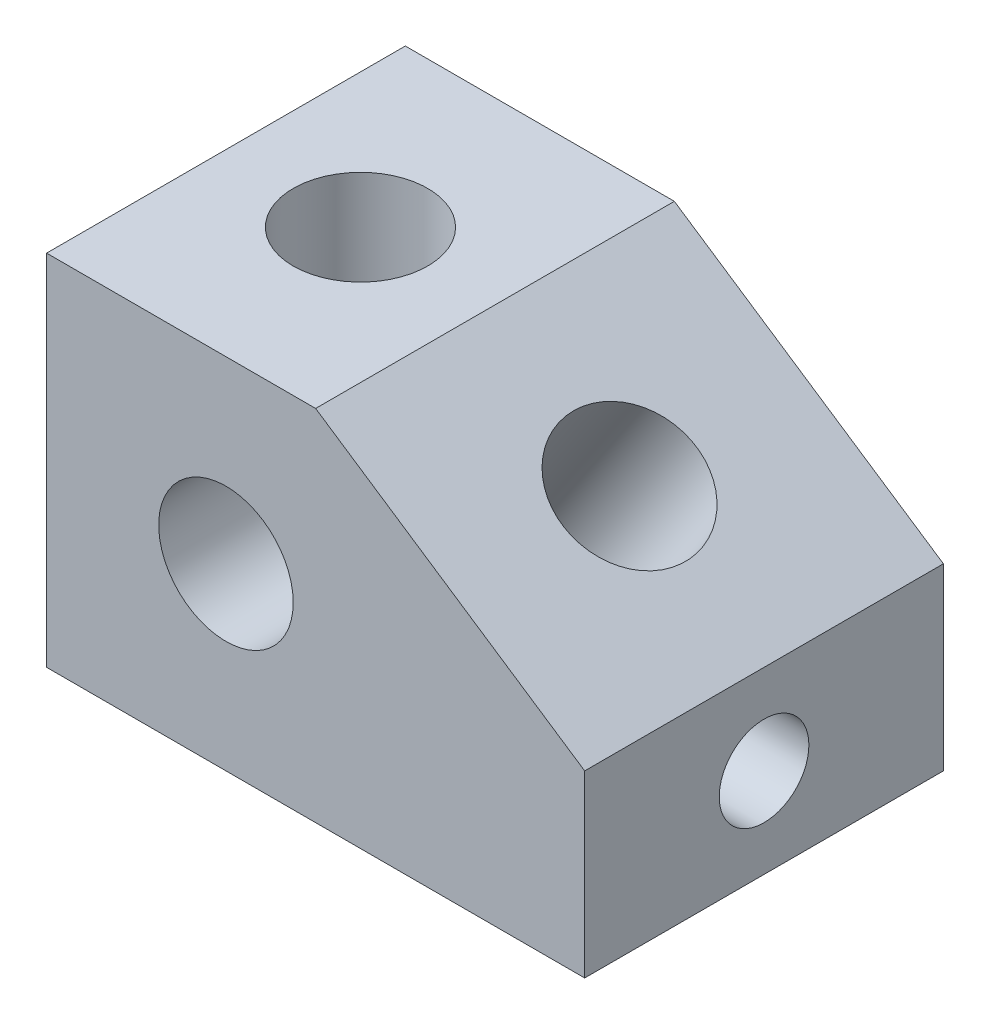
SolidWorks part; units mm, degrees
ref_plane "정면" through (0, 0, 0) normal (0, 0, 1) x (1, 0, 0)
ref_plane "윗면" through (0, 0, 0) normal (0, 1, 0) x (1, 0, 0)
ref_plane "우측면" through (0, 0, 0) normal (1, 0, 0) x (0, 0, -1)
sketch "스케치1" plane through (0, 0, 0) normal (0, 0, 1) x (1, 0, 0)
  line L0 (-34.3086, 0) -> (25.6914, 0)
  line L1 (25.6914, 0) -> (25.6914, 20)
  line L2 (-34.3086, 0) -> (-34.3086, 40)
  line L3 (-34.3086, 40) -> (-4.3086, 40)
  line L4 (-4.3086, 40) -> (25.6914, 20)
  dimension "D1" = 30
  dimension "D2" = 30
  dimension "D3" = 20
  dimension "D4" = 20
extrude "보스-돌출1" add sketch "스케치1" along normal blind 40
sketch "스케치2" plane through (0, 0, 40) normal (0, 0, 1) x (1, 0, 0)
  circle A0 centre (-14.3086, 20) radius 7.5
  point P2 (0, 0)
  dimension "D1" = 20
  dimension "D2" = 15
  dimension "D3" = 20
extrude "컷-돌출1" cut sketch "스케치2" against normal blind 40
sketch "스케치4" plane through (0, 40, 0) normal (0, 1, 0) x (1, 0, 0)
  line L0 (-34.3086, -40) -> (-34.3086, 0) construction
  circle A0 centre (-19.3086, -20) radius 7.5
  point P4 (0, 0)
  point P5 (-19.3086, -20)
  dimension "D1" = 15
  dimension "D2" = 15
  dimension "D3" = 20
extrude "컷-돌출2" cut sketch "스케치4" against normal through all
sketch "스케치5" plane through (25.6914, 0, 0) normal (1, 0, 0) x (0, 0, -1)
  circle A0 centre (-20, 10) radius 5
extrude "컷-돌출3" cut sketch "스케치5" against normal through all
sketch "스케치6" plane through (17.1358, 25.7037, 0) normal (0.5547, 0.8321, 0) x (0.8321, -0.5547, 0)
  circle A0 centre (-7.7452, -20) radius 7.5
extrude "컷-돌출4" cut sketch "스케치6" against normal through all
